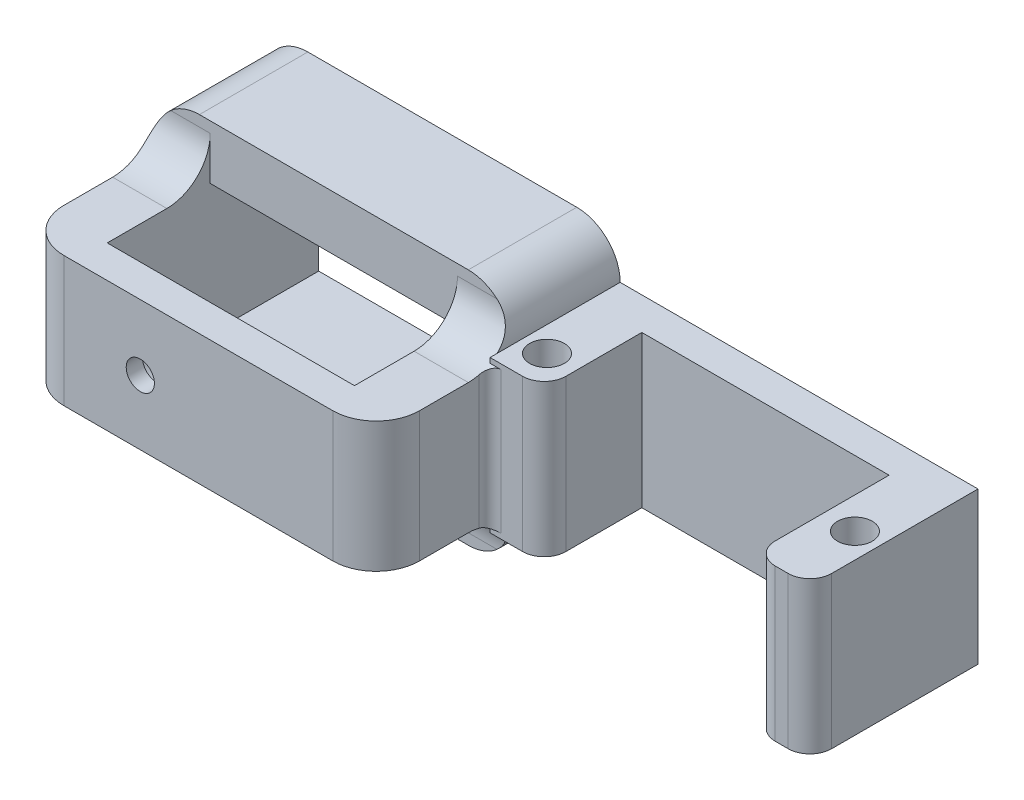
SolidWorks part; units mm, degrees
ref_plane "Front Plane" through (0, 0, 0) normal (0, 0, 1) x (1, 0, 0)
ref_plane "Top Plane" through (0, 0, 0) normal (0, 1, 0) x (1, 0, 0)
ref_plane "Right Plane" through (0, 0, 0) normal (1, 0, 0) x (0, 0, -1)
sketch "Sketch1" plane through (0, 0, 0) normal (0, 0, 1) x (1, 0, 0)
  line L0 (-11.4, 0) -> (11.4, 0)
  line L1 (11.4, 0) -> (11.4, -12)
  line L2 (-11.4, 0) -> (-11.4, -12)
  point P4 (0, 0)
  dimension "D1" = 22.8
  dimension "D2" = 12
  dimension "D3" = 12
extrude "Extrude-Thin1" add sketch "Sketch1" along normal blind 10 thin thin type one direction reverse wall 5
fillet "Fillet1" radius 4 2 edges at (16.4, 5, 5) (-16.4, 5, 5)
sketch "Sketch2" plane through (0, 0, 10) normal (0, 0, 1) x (1, 0, 0)
  line L0 (-16.4, -12) -> (-16.4, 1) construction
  line L1 (-16.4, -12) -> (-11.4, -12)
  line L2 (-16.4, -12) -> (-16.4, 0)
  line L3 (-16.4, 0) -> (-11.4, 0)
  line L4 (-11.4, -12) -> (-11.4, 0)
  line L5 (16.4, -12) -> (11.4, -12) construction
  line L6 (16.4, -12) -> (11.4, -12)
  line L7 (16.4, -12) -> (16.4, 0)
  line L8 (16.4, 0) -> (11.4, 0)
  line L9 (11.4, -12) -> (11.4, 0)
  line L10 (11.4, 0) -> (11.4, -12) construction
extrude "Boss-Extrude1" add sketch "Sketch2" along normal blind 9.5
sketch "Sketch3" plane through (0, 0, 19.5) normal (0, 0, 1) x (1, 0, 0)
  line L0 (-16.4, 0) -> (-16.4, -12) construction
  line L1 (-16.4, -12) -> (16.4, -12)
  line L2 (-16.4, -12) -> (-16.4, 0)
  line L3 (-16.4, 0) -> (16.4, 0)
  line L4 (16.4, -12) -> (16.4, 0)
  line L5 (16.4, -12) -> (16.4, 0) construction
  line L6 (16.4, 1) -> (16.4, 0) construction
extrude "Boss-Extrude2" add sketch "Sketch3" along normal blind 3
fillet "Fillet2" radius 4 4 edges at (13.9, 0, 10) (-13.9, 0, 10) (16.4, -6, 22.5) (-16.4, -6, 22.5)
sketch "Sketch4" plane through (0, 0, 19.5) normal (0, 0, -1) x (-1, 0, 0)
  line L0 (12.4, 5) -> (-12.4, 5) construction
  line L1 (16.4, -12) -> (16.4, 1) construction
  circle A0 centre (5.35, -6.05) radius 1.3
  dimension "D1" = 2.6
  dimension "D2" = 11.05
  dimension "D3" = 11.05
extrude "Cut-Extrude1" cut sketch "Sketch4" against normal blind 3
sketch "Sketch5" plane through (0, 0, 0) normal (0, 0, -1) x (-1, 0, 0)
  line L0 (16.4, -12) -> (16.4, 1) construction
  line L1 (12.4, 5) -> (-12.4, 5) construction
  line L2 (-16.4, 1) -> (-16.4, -12) construction
  circle A0 centre (14.3, -6.05) radius 1.5
  circle A1 centre (-14.1, -6.05) radius 1.5
  dimension "D1" = 3
  dimension "D2" = 2.1
  dimension "D3" = 11.05
  dimension "D4" = 2.3
extrude "Cut-Extrude2" cut sketch "Sketch5" against normal blind 6
sketch "Sketch6" plane through (0, -12, 0) normal (0, -1, 0) x (1, 0, 0)
  line L0 (16.4, 18.5) -> (16.4, 0) construction
  line L1 (16.4, 0) -> (-16.4, 0)
  line L2 (16.4, 0) -> (16.4, 10)
  line L3 (16.4, 10) -> (-16.4, 10)
  line L4 (-16.4, 0) -> (-16.4, 10)
  line L5 (-16.4, 18.5) -> (-16.4, 0) construction
  line L6 (-11.4, 10) -> (11.4, 10) construction
extrude "Boss-Extrude3" add sketch "Sketch6" along normal blind 5
fillet "Fillet3" radius 4 2 edges at (-16.4, -17, 5) (16.4, -17, 5)
fillet "Fillet4" radius 4 2 edges at (13.9, -12, 10) (-13.9, -12, 10)
sketch "Sketch7" plane through (0, 0, 19.5) normal (0, 0, -1) x (-1, 0, 0)
  circle A0 centre (5.35, -6.05) radius 2.75
  dimension "D1" = 5.5
extrude "Cut-Extrude3" cut sketch "Sketch7" against normal blind 1.5
sketch "Sketch9" plane through (16.4, 0, 0) normal (1, 0, 0) x (0, 0, -1)
  line L0 (0, 1) -> (-11.3542, 1) construction
  line L1 (-3, -13) -> (-12, -13)
  line L2 (-3, -13) -> (-3, 1)
  line L3 (-3, 1) -> (-12, 1)
  line L4 (-12, -13) -> (-12, 1)
  dimension "D1" = 3
  dimension "D2" = 9
  dimension "D3" = 14
extrude "Boss-Extrude5" add sketch "Sketch9" along normal blind 5
fillet "Fillet10" radius 1 1 edges at (16.4, -6, 12)
sketch "Sketch12" plane through (0, 0, 0) normal (0, 0, -1) x (-1, 0, 0)
  line L0 (-21.4, 1) -> (-16.4, 1) construction
  line L1 (-16.4, 1) -> (-49.4, 1)
  line L2 (-16.4, 1) -> (-16.4, -13)
  line L3 (-16.4, -13) -> (-49.4, -13)
  line L4 (-49.4, 1) -> (-49.4, -13)
  line L5 (-21.4, -13) -> (-16.4, -13) construction
  arc A0 (-12.4, 5) -> (-16.4, 1) centre (-12.4, 1) ccw construction
  dimension "D1" = 33
extrude "Boss-Extrude7" add sketch "Sketch12" against normal blind 3
sketch "Sketch13" plane through (0, 0, 3) normal (0, 0, 1) x (1, 0, 0)
  line L0 (49.4, 1) -> (49.4, -13) construction
  line L1 (49.4, 1) -> (44.2, 1)
  line L2 (49.4, 1) -> (49.4, -13)
  line L3 (49.4, -13) -> (44.2, -13)
  line L4 (44.2, 1) -> (44.2, -13)
  line L5 (21.4, 1) -> (49.4, 1) construction
  line L6 (49.4, -13) -> (21.4, -13) construction
  dimension "D1" = 5.2
extrude "Boss-Extrude8" add sketch "Sketch13" along normal blind 12.5
fillet "Fillet11" radius 2 1 edges at (21.4, -6, 12)
fillet "Fillet13" radius 2 2 edges at (49.4, -6, 15.5) (44.2, -6, 15.5)
sketch "Sketch14" plane through (0, 1, 0) normal (0, 1, 0) x (1, 0, 0)
  line L0 (49.4, -13.5) -> (49.4, 0) construction
  line L1 (16.4, 0) -> (49.4, 0) construction
  circle A0 centre (18.7, -9.05) radius 1.6
  circle A1 centre (47.1, -9.05) radius 1.6
  dimension "D1" = 3.2
  dimension "D2" = 3.2
  dimension "D3" = 2.3
  dimension "D4" = 30.7
  dimension "D5" = 9.05
  dimension "D6" = 9.05
extrude "Cut-Extrude4" cut sketch "Sketch14" against normal through all
